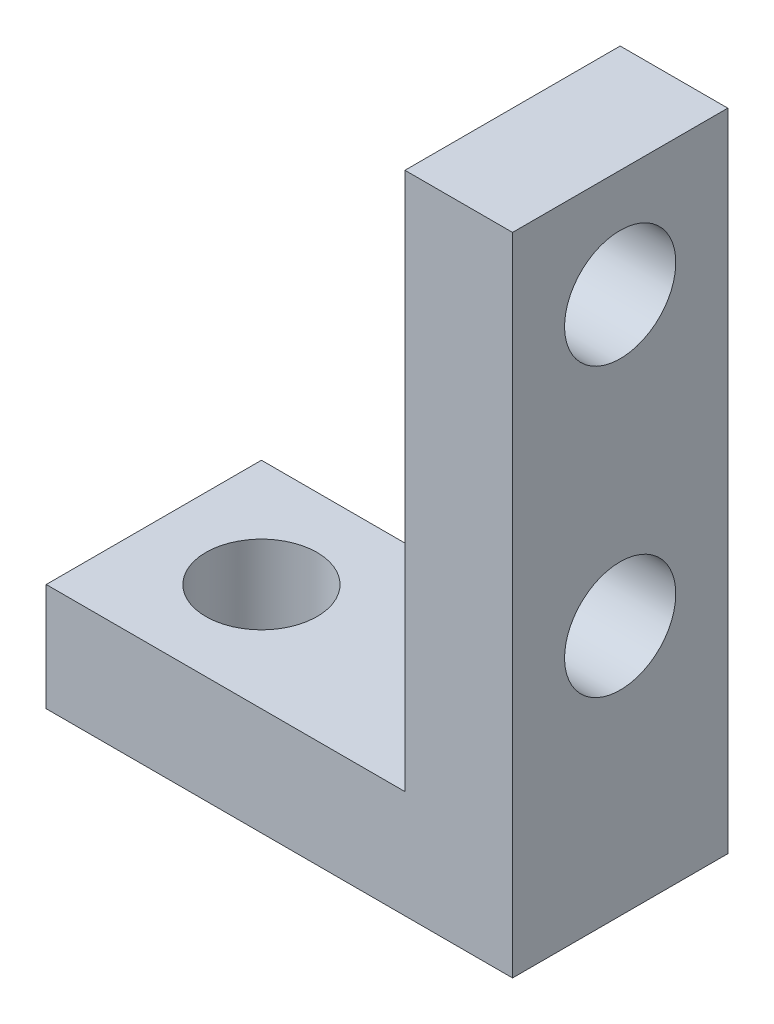
SolidWorks part; units mm, degrees
ref_plane "Front Plane" through (0, 0, 0) normal (0, 0, 1) x (1, 0, 0)
ref_plane "Top Plane" through (0, 0, 0) normal (0, 1, 0) x (1, 0, 0)
ref_plane "Right Plane" through (0, 0, 0) normal (1, 0, 0) x (0, 0, -1)
sketch "Sketch1" plane through (0, 0, 0) normal (0, 0, 1) x (1, 0, 0)
  line L0 (0.5, -6) -> (3.5, -4.7)
  line L1 (6.5, 9) -> (-6.5, 9)
  line L2 (6.5, 9) -> (6.5, -9)
  line L3 (6.5, -9) -> (-6.5, -9)
  line L4 (-6.5, 9) -> (-6.5, -9)
  line L5 (6.5, 9) -> (-6.5, -9) construction
  line L6 (6.5, -9) -> (-6.5, 9) construction
  line L7 (-6.5, 9) -> (3.5, 9)
  line L8 (-6.5, 9) -> (-6.5, -6)
  line L9 (-6.5, -6) -> (3.5, -6)
  line L10 (3.5, 9) -> (3.5, -6)
  point P0 (0, 0)
  dimension "D1" = 13
  dimension "D2" = 18
  dimension "D3" = 3
  dimension "D4" = 3
  dimension "D5" = 1.3
  dimension "D6" = 3
extrude "Boss-Extrude1" add sketch "Sketch1" along normal blind 6 contours L1 L10 L9 L4 L3 L2
sketch "Sketch3" plane through (6.5, 0, 0) normal (1, 0, 0) x (0, 0, -1)
  line L0 (-3, 9) -> (-3, -49991) construction
  line L1 (-6, 9) -> (0, 9) construction
  line L2 (-6, -9) -> (0, -9) construction
  circle A0 centre (-3, 6) radius 1.55
  circle A1 centre (-3, -2) radius 1.55
  point P4 (-3, 9)
  dimension "D1" = 3.1
  dimension "D2" = 3.1
  dimension "D3" = 8
  dimension "D4" = 7
extrude "Cut-Extrude1" cut sketch "Sketch3" against normal through all
sketch "Sketch5" plane through (0, -9, 0) normal (0, -1, 0) x (1, 0, 0)
  line L0 (6.5, 3) -> (-49993.5, 3) construction
  line L1 (6.5, 6) -> (6.5, 0) construction
  line L2 (-6.5, 6) -> (-6.5, 0) construction
  circle A0 centre (-3.5, 3) radius 1.55
  point P4 (6.5, 3)
  dimension "D2" = 3.1
  dimension "D1" = 3
extrude "Cut-Extrude2" cut sketch "Sketch5" against normal through all
